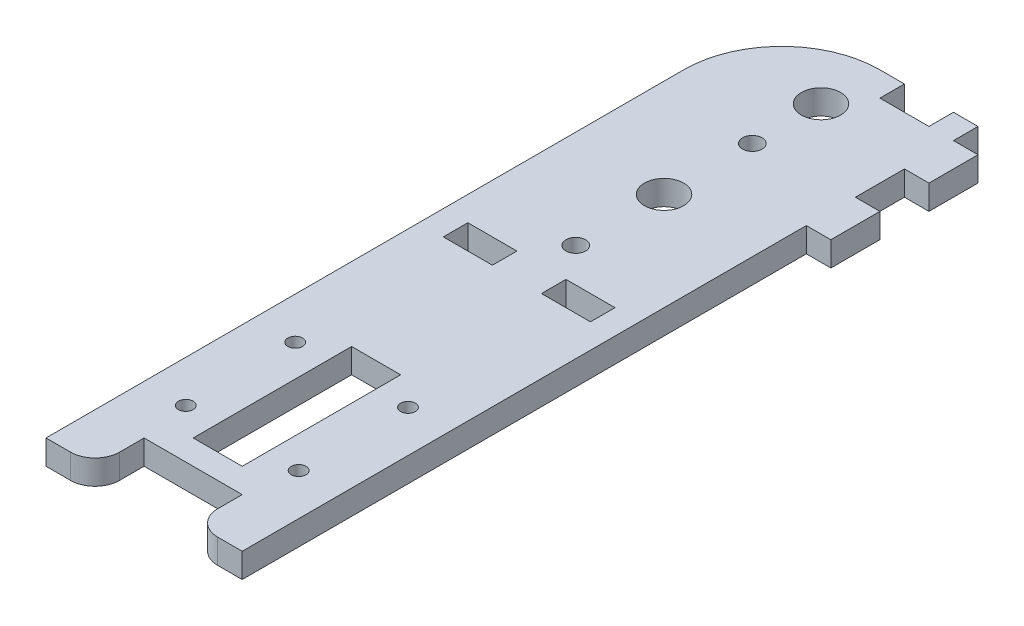
SolidWorks part; units mm, degrees
ref_plane "前视基准面" through (0, 0, 0) normal (0, 0, 1) x (1, 0, 0)
ref_plane "上视基准面" through (0, 0, 0) normal (0, 1, 0) x (1, 0, 0)
ref_plane "右视基准面" through (0, 0, 0) normal (1, 0, 0) x (0, 0, -1)
sketch "草图1" plane through (0, 0, 0) normal (0, 1, 0) x (1, 0, 0)
  line L0 (10, 5) -> (10, 10)
  line L1 (0, 0) -> (5, 0)
  line L2 (0, 0) -> (0, 130)
  line L3 (20, 150) -> (25, 150)
  line L4 (40, 0) -> (40, 115)
  line L5 (10, 10) -> (30, 10)
  line L6 (30, 10) -> (30, 5)
  line L7 (35, 0) -> (40, 0)
  line L8 (-35.4894, 145) -> (63.0619, 145) construction
  line L9 (-37.9463, 138) -> (58.967, 138) construction
  line L10 (-37.9463, 106) -> (65.7919, 106) construction
  line L11 (-37.9463, 81) -> (65.7919, 81) construction
  line L12 (-41.7683, 76) -> (71.7683, 76) construction
  line L13 (20, 145.2242) -> (20, 30.7758) construction
  line L14 (40, 145) -> (40, 150)
  line L15 (25, 150) -> (25, 145)
  line L16 (25, 145) -> (35, 145)
  line L17 (35, 150) -> (35, 145)
  line L18 (5, 81) -> (15, 81)
  line L19 (5, 81) -> (5, 76)
  line L20 (5, 76) -> (15, 76)
  line L21 (15, 81) -> (15, 76)
  line L22 (25, 81) -> (35, 81)
  line L23 (25, 81) -> (25, 76)
  line L24 (25, 76) -> (35, 76)
  line L25 (35, 81) -> (35, 76)
  line L26 (45, 169.5111) -> (45, 60.4889) construction
  line L27 (35, 150) -> (40, 150)
  line L28 (40, 145) -> (45, 145)
  line L29 (40, 125) -> (40, 135)
  line L30 (40, 135) -> (45, 135)
  line L31 (45, 145) -> (45, 135)
  line L32 (40, 125) -> (45, 125)
  line L33 (-8.3125, 15) -> (58.3125, 15) construction
  line L34 (40, 115) -> (45, 115)
  line L35 (45, 125) -> (45, 115)
  line L36 (-8.3125, 20) -> (58.967, 20) construction
  line L37 (-8.3125, 42.3) -> (58.967, 42.3) construction
  line L38 (-8.3125, 47.3) -> (57.6308, 47.3) construction
  line L39 (8.5, 56.8376) -> (8.5, 12.2834) construction
  line L40 (31.5, 60.4889) -> (31.5, 12.2834) construction
  line L42 (15, 47.3) -> (25, 47.3)
  line L43 (15, 47.3) -> (15, 15)
  line L44 (15, 15) -> (25, 15)
  line L45 (25, 47.3) -> (25, 15)
  circle A0 centre (20, 138) radius 4
  circle A1 centre (20, 106) radius 4
  circle A2 centre (20, 124) radius 2
  circle A3 centre (20, 88) radius 2
  circle A4 centre (8.5, 42.3) radius 1.5
  circle A5 centre (31.5, 42.3) radius 1.5
  circle A6 centre (8.5, 20) radius 1.5
  circle A7 centre (31.5, 20) radius 1.5
  arc A8 (30, 5) -> (35, 0) centre (35, 5) ccw
  arc A9 (10, 5) -> (5, 0) centre (5, 5) cw
  arc A10 (0, 130) -> (20, 150) centre (20, 130) cw
  point P77 (30, 0)
  point P80 (10, 0)
  point P83 (0, 150)
  dimension "D18" = 18
  dimension "D33" = 5
  dimension "D34" = 20
  dimension "D1" = 150
  dimension "D2" = 40
  dimension "D3" = 10
  dimension "D4" = 10
  dimension "D5" = 10
  dimension "D6" = 5
  dimension "D7" = 7
  dimension "D8" = 32
  dimension "D9" = 25
  dimension "D10" = 5
  dimension "D11" = 10
  dimension "D12" = 10
  dimension "D13" = 5
  dimension "D14" = 5
  dimension "D15" = 5
  dimension "D16" = 10
  dimension "D17" = 20
  dimension "D19" = 18
  dimension "D20" = 5
  dimension "D21" = 5
  dimension "D22" = 10
  dimension "D23" = 10
  dimension "D24" = 10
  dimension "D25" = 5
  dimension "D26" = 32.3
  dimension "D27" = 5
  dimension "D28" = 10
  dimension "D29" = 32.3
  dimension "D30" = 5
  dimension "D31" = 6.5
  dimension "D32" = 6.5
extrude "凸台-拉伸1" add sketch "草图1" along normal blind 5
